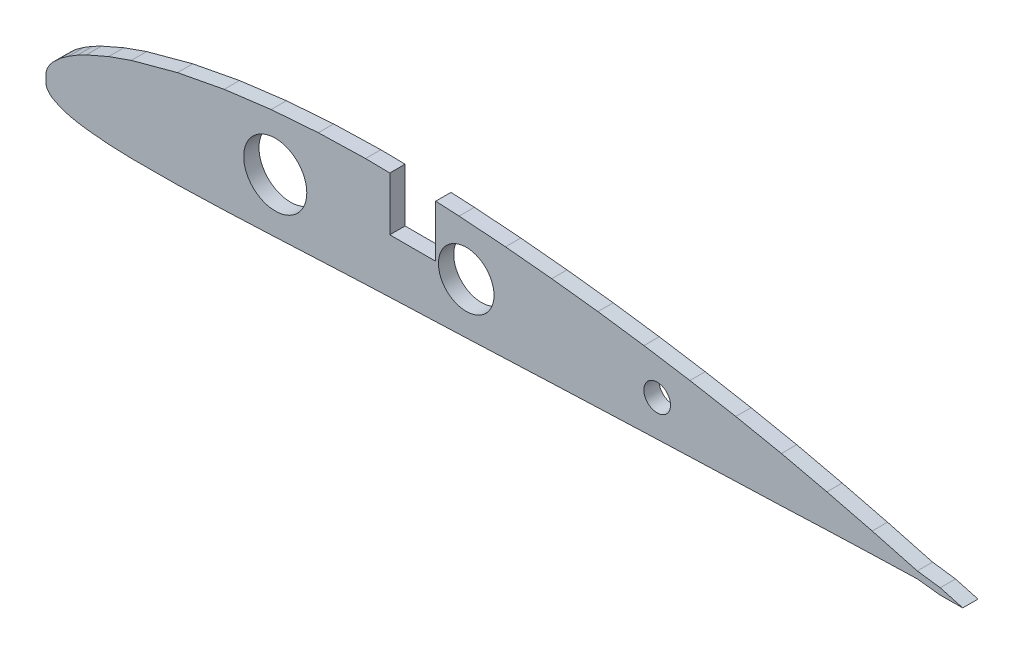
SolidWorks part; units mm, degrees
ref_plane "前视基准面" through (0, 0, 0) normal (0, 0, 1) x (1, 0, 0)
ref_plane "上视基准面" through (0, 0, 0) normal (0, 1, 0) x (1, 0, 0)
ref_plane "右视基准面" through (0, 0, 0) normal (1, 0, 0) x (0, 0, -1)
sketch "草图1" plane through (0, 0, 0) normal (0, 0, 1) x (1, 0, 0)
  line L0 (0, 0) -> (-0.022, 1.356)
  line L1 (-0.022, 1.356) -> (0.112, 1.935)
  line L2 (0.112, 1.935) -> (0.273, 2.386)
  line L3 (0.273, 2.386) -> (0.631, 3.114)
  line L4 (0.631, 3.114) -> (1.112, 3.853)
  line L5 (1.112, 3.853) -> (1.618, 4.487)
  line L6 (1.618, 4.487) -> (3.738, 6.498)
  line L7 (3.738, 6.498) -> (5.954, 8.087)
  line L8 (5.954, 8.087) -> (8.221, 9.446)
  line L9 (8.221, 9.446) -> (10.524, 10.652)
  line L10 (10.524, 10.652) -> (16.38, 13.212)
  line L11 (16.38, 13.212) -> (22.333, 15.314)
  line L12 (22.333, 15.314) -> (34.409, 18.579)
  line L13 (34.409, 18.579) -> (46.63, 20.902)
  line L14 (46.63, 20.902) -> (58.933, 22.468)
  line L15 (58.933, 22.468) -> (71.28, 23.384)
  line L16 (71.28, 23.384) -> (83.643, 23.716)
  line L17 (83.643, 23.716) -> (96, 23.519)
  line L18 (96, 23.519) -> (108.149, 22.918)
  line L19 (108.149, 22.918) -> (120.282, 22.016)
  line L20 (120.282, 22.016) -> (132.395, 20.844)
  line L21 (132.395, 20.844) -> (144.485, 19.431)
  line L22 (144.485, 19.431) -> (156.547, 17.759)
  line L23 (156.547, 17.759) -> (168.577, 15.85)
  line L24 (168.577, 15.85) -> (180.573, 13.692)
  line L25 (180.573, 13.692) -> (192.529, 11.275)
  line L26 (192.529, 11.275) -> (204.433, 8.534)
  line L27 (204.433, 8.534) -> (216.296, 5.59)
  line L28 (216.296, 5.59) -> (228.111, 2.437)
  line L29 (228.111, 2.437) -> (234.107, 1.62)
  line L30 (234.107, 1.62) -> (240, 0)
  line L31 (240, 0) -> (234.107, -0.054)
  line L32 (234.107, -0.054) -> (228.111, 0.629)
  line L33 (228.111, 0.629) -> (216.296, 0.276)
  line L34 (216.296, 0.276) -> (204.433, -0.134)
  line L35 (204.433, -0.134) -> (192.529, -0.609)
  line L36 (192.529, -0.609) -> (180.573, -1.026)
  line L37 (180.573, -1.026) -> (168.577, -1.45)
  line L38 (168.577, -1.45) -> (156.547, -1.893)
  line L39 (156.547, -1.893) -> (144.485, -2.365)
  line L40 (144.485, -2.365) -> (132.395, -2.844)
  line L41 (132.395, -2.844) -> (120.282, -3.35)
  line L42 (120.282, -3.35) -> (108.149, -3.852)
  line L43 (108.149, -3.852) -> (96, -4.319)
  line L44 (96, -4.319) -> (83.643, -4.816)
  line L45 (83.643, -4.816) -> (71.28, -5.384)
  line L46 (71.28, -5.384) -> (58.933, -5.968)
  line L47 (58.933, -5.968) -> (46.63, -6.502)
  line L48 (46.63, -6.502) -> (34.409, -6.879)
  line L49 (34.409, -6.879) -> (22.333, -6.914)
  line L50 (22.333, -6.914) -> (16.38, -6.687)
  line L51 (16.38, -6.687) -> (10.524, -6.152)
  line L52 (10.524, -6.152) -> (8.221, -5.798)
  line L53 (8.221, -5.798) -> (5.954, -5.315)
  line L54 (5.954, -5.315) -> (3.738, -4.626)
  line L55 (3.738, -4.626) -> (1.618, -3.539)
  line L56 (1.618, -3.539) -> (1.112, -3.14)
  line L57 (1.112, -3.14) -> (0.631, -2.636)
  line L58 (0.631, -2.636) -> (0.273, -2.099)
  line L59 (0.273, -2.099) -> (0.112, -1.743)
  line L60 (0.112, -1.743) -> (-0.022, -1.26)
  line L61 (-0.022, -1.26) -> (0, 0)
extrude "凸台-拉伸1" add sketch "草图1" along normal blind 4
sketch "草图2" plane through (0, 0, 0) normal (0, 0, 1) x (1, 0, 0)
  circle A0 centre (60, 8.25) radius 8.2578
extrude "切除-拉伸1" cut sketch "草图2" along normal through all
sketch "草图3" plane through (0, 0, 0) normal (0, 0, 1) x (1, 0, 0)
  line L0 (90, 9.6) -> (102, 9.6)
  line L1 (102, 9.6) -> (102, 24.6)
  line L2 (102, 24.6) -> (90, 24.6)
  line L3 (90, 24.6) -> (90, 9.6)
extrude "切除-拉伸2" cut sketch "草图3" along normal through all
sketch "草图4" plane through (0, 0, 0) normal (0, 0, 1) x (1, 0, 0)
  circle A0 centre (110, 9.5093) radius 7.273
extrude "切除-拉伸3" cut sketch "草图4" along normal through all
sketch "草图5" plane through (0, 0, 0) normal (0, 0, 1) x (1, 0, 0)
  circle A0 centre (160, 7.7037) radius 3.493
extrude "切除-拉伸4" cut sketch "草图5" along normal through all
